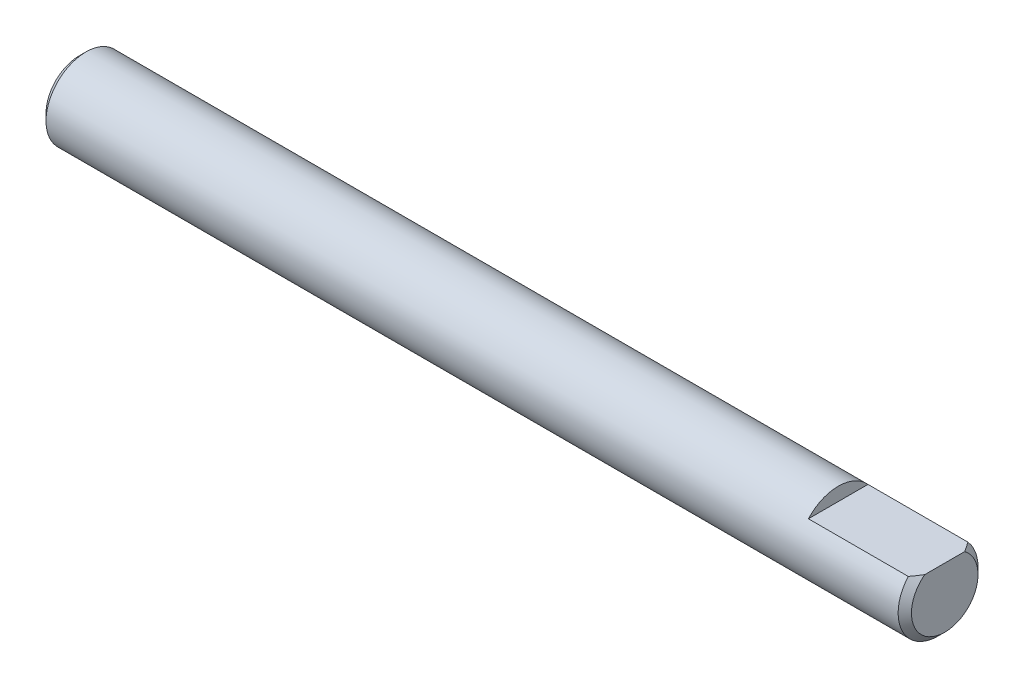
SolidWorks part; units mm, degrees
material "Wrought Stainless Steel"
ref_plane "Front Plane" through (0, 0, 0) normal (0, 0, 1) x (1, 0, 0)
ref_plane "Top Plane" through (0, 0, 0) normal (0, 1, 0) x (1, 0, 0)
ref_plane "Right Plane" through (0, 0, 0) normal (1, 0, 0) x (0, 0, -1)
sketch "Sketch1" plane through (0, 0, 0) normal (1, 0, 0) x (0, 0, -1)
  circle A0 centre (0, 0) radius 3
  dimension "D1" = 6
extrude "Boss-Extrude1" add sketch "Sketch1" along normal mid plane 65
chamfer "Chamfer1" distance 0.5 angle 45 2 edges at (32.5, 0, -3) (-32.5, 0, -3)
sketch "Sketch2" plane through (32.5, 0, 0) normal (1, 0, 0) x (0, 0, -1)
  line L0 (-2.2361, 2) -> (2.2361, 2)
  arc A0 (2.2361, 2) -> (-2.2361, 2) centre (0, 0) ccw
  dimension "D2" = 6
  dimension "D1" = 2
extrude "Cut-Extrude1" cut sketch "Sketch2" against normal blind 8
